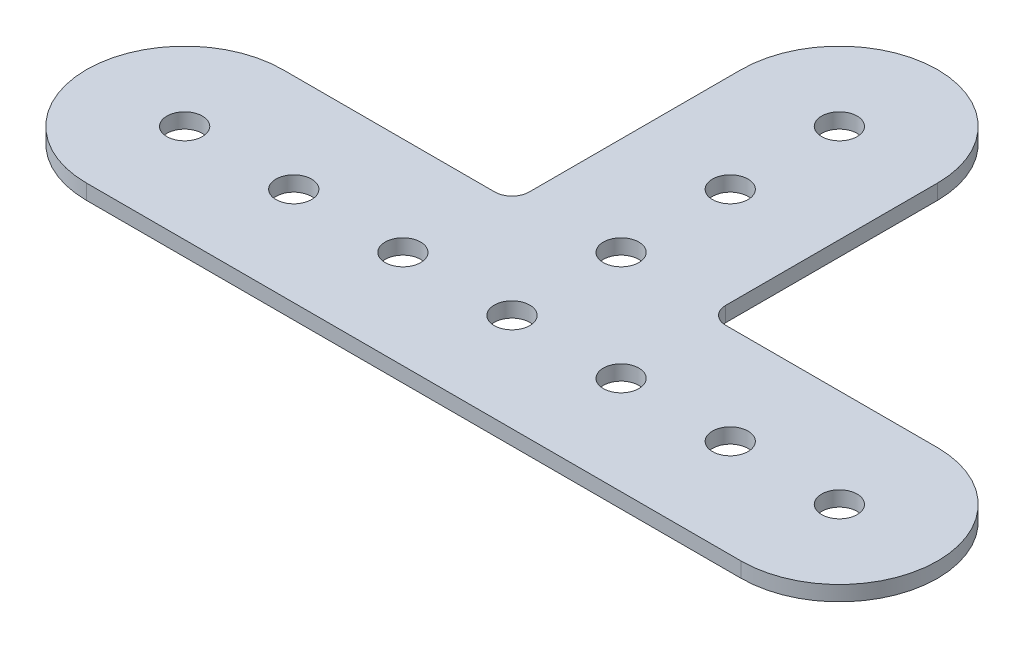
SolidWorks part; units mm, degrees
ref_plane "Front Plane" through (0, 0, 0) normal (0, 0, 1) x (1, 0, 0)
ref_plane "Top Plane" through (0, 0, 0) normal (0, 1, 0) x (1, 0, 0)
ref_plane "Right Plane" through (0, 0, 0) normal (1, 0, 0) x (0, 0, -1)
sketch "Sketch1" plane through (0, 0, 0) normal (0, 1, 0) x (1, 0, 0)
  line L0 (0, 0) -> (38.1, 0) construction
  line L1 (0, -55) -> (0, 55) construction
  line L2 (0, 0) -> (0, 38.1) construction
  line L3 (-38.1, -11.43) -> (38.1, -11.43)
  line L4 (-38.1, 11.43) -> (38.1, 11.43)
  line L5 (-11.43, 38.1) -> (-11.43, 11.43)
  line L6 (11.43, 38.1) -> (11.43, 11.43)
  circle A0 centre (0, 0) radius 2.07
  circle A1 centre (12.7, 0) radius 2.07
  circle A2 centre (25.4, 0) radius 2.07
  circle A3 centre (38.1, 0) radius 2.07
  circle A4 centre (-12.7, 0) radius 2.07
  circle A5 centre (-25.4, 0) radius 2.07
  circle A6 centre (-38.1, 0) radius 2.07
  circle A7 centre (0, 12.7) radius 2.07
  circle A8 centre (0, 25.4) radius 2.07
  circle A9 centre (0, 38.1) radius 2.07
  circle A10 centre (0, 38.1) radius 11.43
  circle A11 centre (-38.1, 0) radius 11.43
  circle A12 centre (38.1, 0) radius 11.43
  dimension "D1" = 4.14
  dimension "D4" = 12.7
  dimension "D8" = 22.86
  dimension "D2" = 38.1
  dimension "D5" = 38.1
  dimension "D7" = 12.7
  dimension "D3" = 4
  dimension "D6" = 4
extrude "Boss-Extrude1" add sketch "Sketch1" along normal mid plane 1.75 contours A11 A5 A6 | A12 L4 A7 A11 A5 L3 A2 A0 A1 A4 | A12 A2 A3 | A8 A10 A9 | A10 A8 L5 L4 A7 L6
fillet "Fillet1" radius 2 2 edges at (-11.43, 0, -11.43) (11.43, 0, -11.43)
